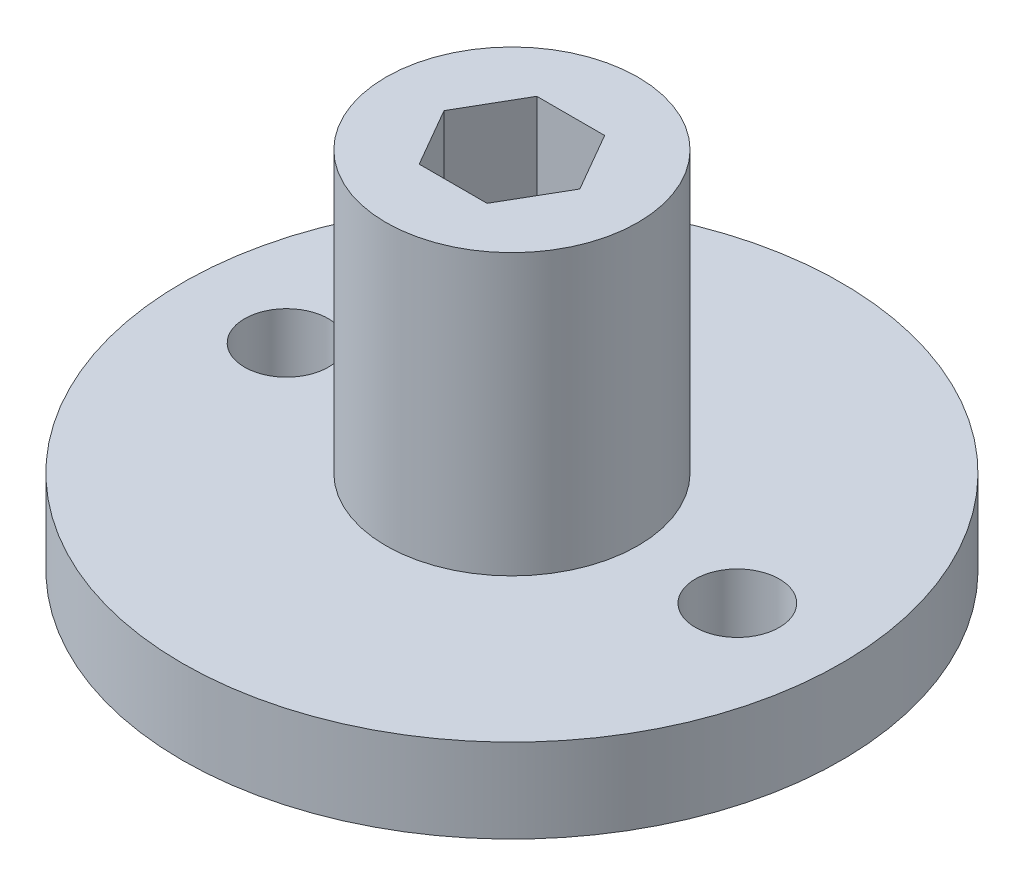
SolidWorks part; units mm, degrees
material "Pure Silver"
ref_plane "Front Plane" through (0, 0, 0) normal (0, 0, 1) x (1, 0, 0)
ref_plane "Top Plane" through (0, 0, 0) normal (0, 1, 0) x (1, 0, 0)
ref_plane "Right Plane" through (0, 0, 0) normal (1, 0, 0) x (0, 0, -1)
sketch "Sketch1" plane through (0, 0, 0) normal (0, 1, 0) x (1, 0, 0)
  circle A0 centre (0, 0) radius 11.7729
  circle A1 centre (0, 0) radius 1.016
  dimension "D1" = 23.5458
  dimension "D2" = 2.032
extrude "Boss-Extrude1" add sketch "Sketch1" along normal blind 3
sketch "Sketch2" plane through (0, 3, 0) normal (0, 1, 0) x (1, 0, 0)
  line L0 (0, 0) -> (8.0518, 0) construction
  line L1 (-8.0518, 0) -> (0, 0) construction
  circle A0 centre (8.0518, 0) radius 1.5
  circle A1 centre (-8.0518, 0) radius 1.5
  dimension "D2" = 3
  dimension "D1" = 16.1036
extrude "Cut-Extrude1" cut sketch "Sketch2" against normal through all
sketch "Sketch4" plane through (0, 0, 0) normal (0, -1, 0) x (1, 0, 0)
  circle A0 centre (0, 0) radius 3
  dimension "D1" = 6
extrude "Cut-Extrude3" cut sketch "Sketch4" against normal blind 1.5 contours A0
sketch "Sketch6" plane through (0, 3, 0) normal (0, 1, 0) x (1, 0, 0)
  circle A0 centre (0, 0) radius 4.5
  dimension "D1" = 9
extrude "Boss-Extrude4" add sketch "Sketch6" along normal blind 10
sketch "Sketch7" plane through (0, 3, 0) normal (0, -1, 0) x (1, 0, 0)
  line L1 (2.4249, 0) -> (1.2124, 2.1)
  line L2 (1.2124, 2.1) -> (-1.2124, 2.1)
  line L3 (-1.2124, 2.1) -> (-2.4249, 0)
  line L4 (-2.4249, 0) -> (-1.2124, -2.1)
  line L5 (-1.2124, -2.1) -> (1.2124, -2.1)
  line L6 (1.2124, -2.1) -> (2.4249, 0)
  circle A0 centre (0, 0) radius 2.1 construction
extrude "Cut-Extrude4" cut sketch "Sketch7" against normal through all
